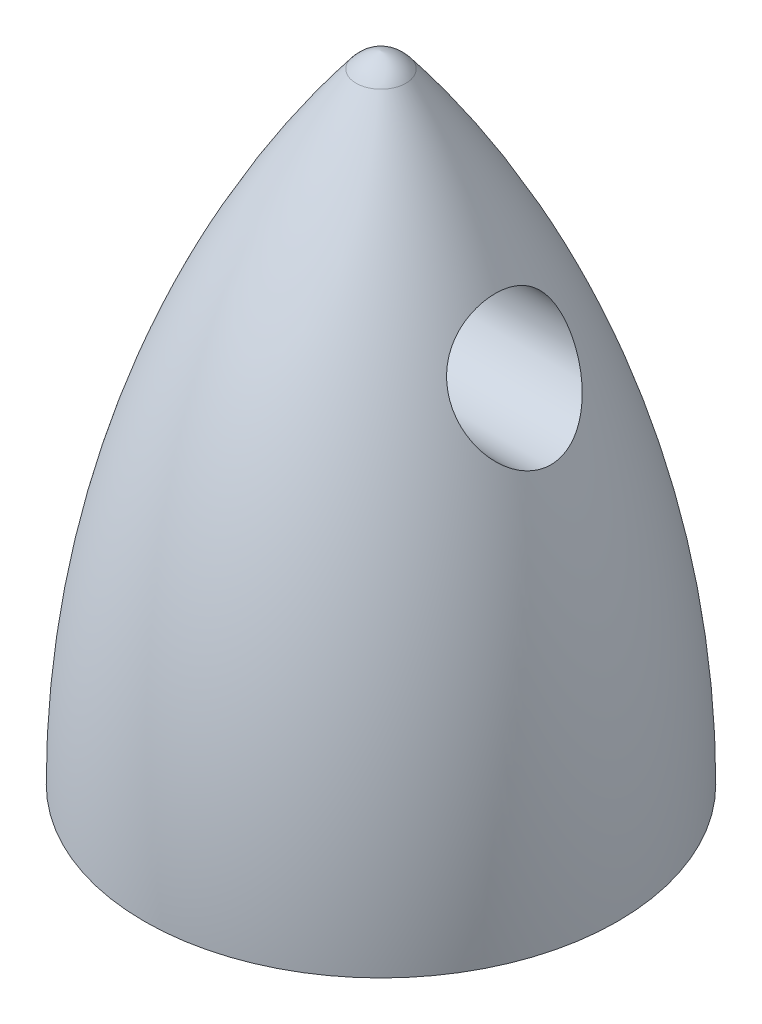
SolidWorks part; units mm, degrees
ref_plane "Front Plane" through (0, 0, 0) normal (0, 0, 1) x (1, 0, 0)
ref_plane "Top Plane" through (0, 0, 0) normal (0, 1, 0) x (1, 0, 0)
ref_plane "Right Plane" through (0, 0, 0) normal (1, 0, 0) x (0, 0, -1)
sketch "Sketch1" plane through (0, 0, 0) normal (1, 0, 0) x (0, 0, -1)
  line L0 (0, 0) -> (0, 67.3418) construction
  line L1 (0, 0) -> (5.885, 0)
  line L2 (0, 15.7979) -> (0, 0)
  arc A0 (5.885, 0) -> (0.6197, 15.4129) centre (-19.3065, 0) ccw
  arc A1 (0.6197, 15.4129) -> (0, 15.7979) centre (-0.2071, 14.7734) ccw
  dimension "D1" = 11.77
revolve "Revolve1" add sketch "Sketch1" angle 360 about L0
sketch "Sketch2" plane through (0, 0, 0) normal (0, -1, 0) x (1, 0, 0)
  circle A0 centre (0, 0) radius 2.15
  dimension "D1" = 4.3
extrude "Cut-Extrude1" cut sketch "Sketch2" against normal blind 8.128
sketch "Sketch3" plane through (0, 0, 0) normal (1, 0, 0) x (0, 0, -1)
  line L0 (0, 0) -> (0, 15.7979) construction
  line L1 (-5.885, 0) -> (5.885, 0) construction
  circle A0 centre (0, 10.5) radius 1.5
  dimension "D2" = 3
  dimension "D1" = 10.5
extrude "Cut-Extrude2" cut sketch "Sketch3" against normal through all and the other way through all
